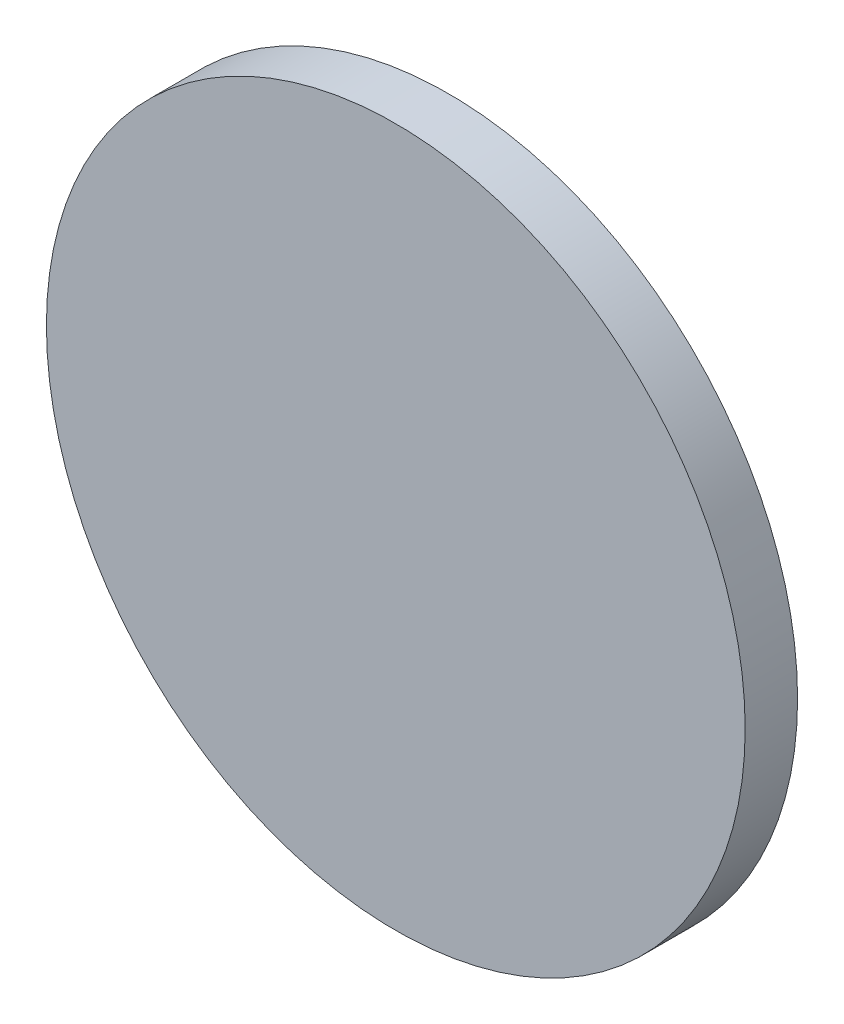
SolidWorks part; units mm, degrees
ref_plane "Front Plane" through (0, 0, 0) normal (0, 0, 1) x (1, 0, 0)
ref_plane "Top Plane" through (0, 0, 0) normal (0, 1, 0) x (1, 0, 0)
ref_plane "Right Plane" through (0, 0, 0) normal (1, 0, 0) x (0, 0, -1)
sketch "Sketch1" plane through (0, 0, 0) normal (0, 0, 1) x (1, 0, 0)
  circle A0 centre (0, 0) radius 100
  dimension "D1" = 200
extrude "Boss-Extrude1" add sketch "Sketch1" along normal blind 15
